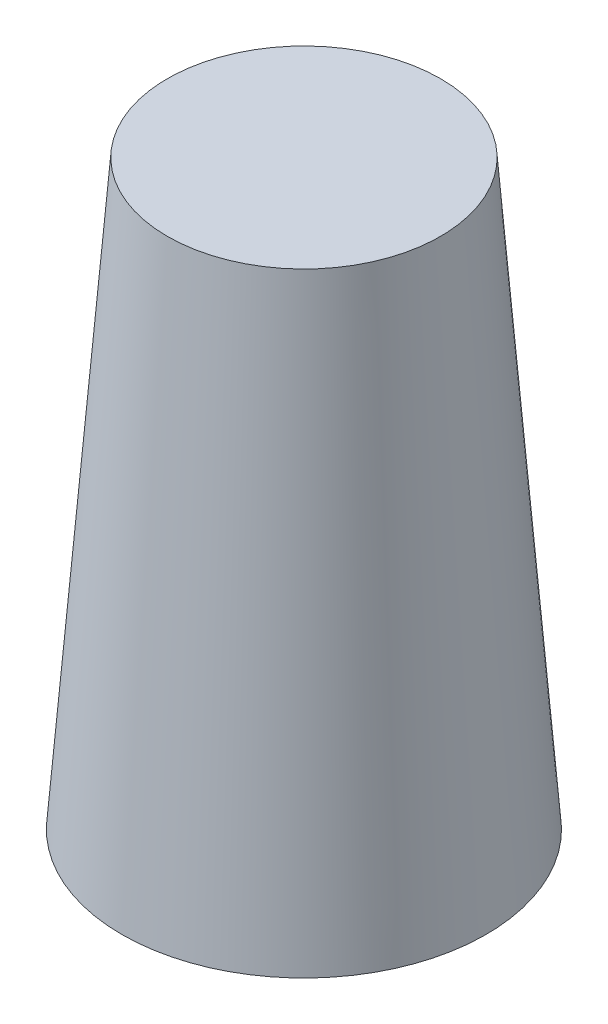
SolidWorks part; units mm, degrees
material "PVB"
ref_plane "Plan de face" through (0, 0, 0) normal (0, 0, 1) x (1, 0, 0)
ref_plane "Plan de dessus" through (0, 0, 0) normal (0, 1, 0) x (1, 0, 0)
ref_plane "Plan de droite" through (0, 0, 0) normal (1, 0, 0) x (0, 0, -1)
sketch "Esquisse1" plane through (0, 0, 0) normal (0, 0, 1) x (1, 0, 0)
  line L0 (0, 0) -> (-36, 0)
  line L1 (-36, 0) -> (-27, 115)
  line L2 (-27, 115) -> (0, 115)
  line L3 (0, 115) -> (0, 0) construction
  line L4 (0, 0) -> (0, 115)
  dimension "D1" = 115
  dimension "D2" = 72
  dimension "D3" = 54
revolve "Révolution1" add sketch "Esquisse1" angle 360 about L3
shell "Coque1" thickness 1.5
